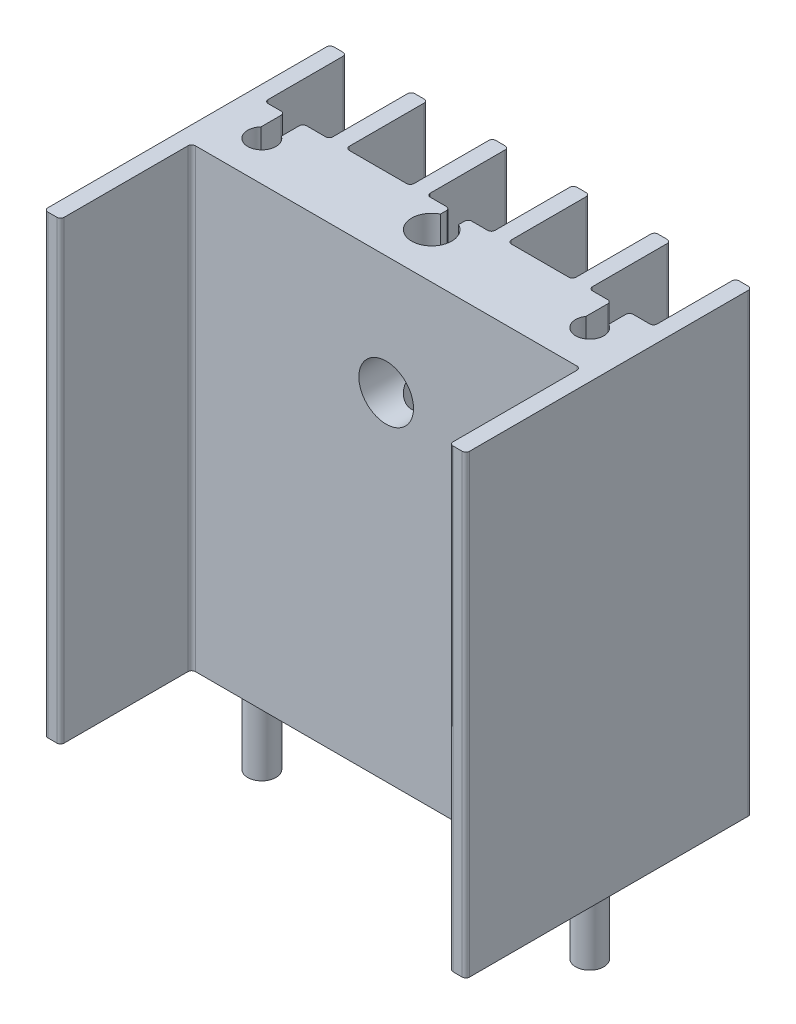
SolidWorks part; units mm, degrees
ref_plane "前视基准面" through (0, 0, 0) normal (0, 0, 1) x (1, 0, 0)
ref_plane "上视基准面" through (0, 0, 0) normal (0, 1, 0) x (1, 0, 0)
ref_plane "右视基准面" through (0, 0, 0) normal (1, 0, 0) x (0, 0, -1)
sketch "草图1" plane through (0, 0, 0) normal (0, 1, 0) x (1, 0, 0)
  line L0 (-11.375, -7.85) -> (-10.875, -7.85)
  line L1 (-11.575, -7.85) -> (11.575, -7.85) construction
  line L2 (-11.575, -7.65) -> (-11.575, 7.65)
  line L3 (-11.575, 7.85) -> (11.575, 7.85) construction
  line L4 (11.575, -7.65) -> (11.575, 7.65)
  line L5 (-11.575, -7.85) -> (11.575, 7.85) construction
  line L6 (-11.575, 7.85) -> (11.575, -7.85) construction
  line L7 (-10.675, -7.65) -> (-10.675, -0.65)
  line L8 (11.375, -7.85) -> (10.875, -7.85)
  line L9 (10.675, -7.65) -> (10.675, -0.65)
  line L10 (10.675, -0.65) -> (-10.675, -0.65)
  line L11 (-11.375, 7.85) -> (-10.875, 7.85)
  line L12 (-10.675, 7.65) -> (-10.675, 3.55)
  line L13 (-10.475, 3.35) -> (-9.7702, 3.35)
  line L14 (11.375, 7.85) -> (10.875, 7.85)
  line L15 (10.675, 7.65) -> (10.675, 3.55)
  line L16 (10.475, 3.35) -> (9.5581, 3.35)
  line L17 (7.125, 3.55) -> (7.125, 7.65)
  line L18 (6.925, 7.85) -> (6.425, 7.85)
  line L19 (-7.125, 3.55) -> (-7.125, 7.65)
  line L20 (-6.925, 7.85) -> (-6.425, 7.85)
  line L21 (-7.125, 3.35) -> (7.125, 3.35) construction
  line L22 (-6.225, 7.65) -> (-6.225, 3.55)
  line L23 (6.225, 7.65) -> (6.225, 3.55)
  line L24 (6.025, 3.35) -> (2.875, 3.35)
  line L25 (-6.025, 3.35) -> (-2.875, 3.35)
  line L26 (-2.675, 3.55) -> (-2.675, 7.65)
  line L27 (-2.475, 7.85) -> (-1.975, 7.85)
  line L28 (2.675, 3.55) -> (2.675, 7.65)
  line L29 (2.475, 7.85) -> (1.975, 7.85)
  line L30 (-1.775, 7.65) -> (-1.775, 3.55)
  line L31 (-1.575, 3.35) -> (-0.7, 3.35)
  line L32 (1.775, 3.55) -> (1.775, 7.65)
  line L33 (0, -0.65) -> (0, 1.85) construction
  line L34 (0, 7.85) -> (0, -7.85) construction
  line L36 (-0.5, 3.15) -> (-0.5, 2.8298)
  line L37 (0.5, 3.15) -> (0.5, 2.8298)
  line L38 (0.7, 3.35) -> (1.575, 3.35)
  line L40 (-9.5702, 3.15) -> (-9.5702, 2.0499)
  line L41 (-8.5702, 3.15) -> (-8.5702, 2.1699)
  line L42 (-8.3702, 3.35) -> (-7.325, 3.35)
  line L43 (8.1581, 3.35) -> (7.325, 3.35)
  line L44 (8.3581, 3.15) -> (8.3581, 1.9593)
  line L45 (9.3581, 3.15) -> (9.3581, 2.2123)
  arc A0 (-0.5, 2.8298) -> (0.5, 2.8298) centre (0, 1.85) ccw
  arc A1 (8.3581, 1.9593) -> (9.3581, 2.2123) centre (9, 1.525) ccw
  arc A2 (-8.5702, 2.1699) -> (-9.5702, 2.0499) centre (-9, 1.525) cw
  arc A3 (-10.675, 3.55) -> (-10.475, 3.35) centre (-10.475, 3.55) ccw
  arc A4 (-7.325, 3.35) -> (-7.125, 3.55) centre (-7.325, 3.55) ccw
  arc A5 (-6.225, 3.55) -> (-6.025, 3.35) centre (-6.025, 3.55) ccw
  arc A6 (-2.875, 3.35) -> (-2.675, 3.55) centre (-2.875, 3.55) ccw
  arc A7 (-1.775, 3.55) -> (-1.575, 3.35) centre (-1.575, 3.55) ccw
  arc A8 (1.575, 3.35) -> (1.775, 3.55) centre (1.575, 3.55) ccw
  arc A9 (2.875, 3.35) -> (2.675, 3.55) centre (2.875, 3.55) cw
  arc A10 (6.225, 3.55) -> (6.025, 3.35) centre (6.025, 3.55) cw
  arc A11 (7.325, 3.35) -> (7.125, 3.55) centre (7.325, 3.55) cw
  arc A12 (10.675, 3.55) -> (10.475, 3.35) centre (10.475, 3.55) cw
  arc A13 (9.3581, 3.15) -> (9.5581, 3.35) centre (9.5581, 3.15) cw
  arc A14 (8.3581, 3.15) -> (8.1581, 3.35) centre (8.1581, 3.15) ccw
  arc A15 (-9.7702, 3.35) -> (-9.5702, 3.15) centre (-9.7702, 3.15) cw
  arc A16 (-8.3702, 3.35) -> (-8.5702, 3.15) centre (-8.3702, 3.15) ccw
  arc A17 (-0.7, 3.35) -> (-0.5, 3.15) centre (-0.7, 3.15) cw
  arc A18 (0.7, 3.35) -> (0.5, 3.15) centre (0.7, 3.15) ccw
  arc A19 (-11.375, -7.85) -> (-11.575, -7.65) centre (-11.375, -7.65) cw
  arc A20 (-10.875, -7.85) -> (-10.675, -7.65) centre (-10.875, -7.65) ccw
  arc A21 (10.875, -7.85) -> (10.675, -7.65) centre (10.875, -7.65) cw
  arc A22 (11.375, -7.85) -> (11.575, -7.65) centre (11.375, -7.65) ccw
  arc A23 (11.375, 7.85) -> (11.575, 7.65) centre (11.375, 7.65) cw
  arc A24 (10.875, 7.85) -> (10.675, 7.65) centre (10.875, 7.65) ccw
  arc A25 (7.125, 7.65) -> (6.925, 7.85) centre (6.925, 7.65) ccw
  arc A26 (6.425, 7.85) -> (6.225, 7.65) centre (6.425, 7.65) ccw
  arc A27 (2.675, 7.65) -> (2.475, 7.85) centre (2.475, 7.65) ccw
  arc A28 (1.975, 7.85) -> (1.775, 7.65) centre (1.975, 7.65) ccw
  arc A29 (-1.975, 7.85) -> (-1.775, 7.65) centre (-1.975, 7.65) cw
  arc A30 (-2.675, 7.65) -> (-2.475, 7.85) centre (-2.475, 7.65) cw
  arc A31 (-6.425, 7.85) -> (-6.225, 7.65) centre (-6.425, 7.65) cw
  arc A32 (-7.125, 7.65) -> (-6.925, 7.85) centre (-6.925, 7.65) cw
  arc A33 (-10.875, 7.85) -> (-10.675, 7.65) centre (-10.875, 7.65) cw
  arc A34 (-11.575, 7.65) -> (-11.375, 7.85) centre (-11.375, 7.65) cw
  point P0 (0, 0)
  point P33 (9, 1.525)
  point P43 (0, 3.35)
  point P47 (-9.0702, 3.35)
  point P51 (8.8581, 3.35)
  point P54 (-10.675, 3.35)
  point P60 (-6.225, 3.35)
  point P63 (-2.675, 3.35)
  point P66 (-1.775, 3.35)
  point P69 (1.775, 3.35)
  point P72 (2.675, 3.35)
  point P75 (6.225, 3.35)
  point P81 (10.675, 3.35)
  point P84 (9.3581, 3.35)
  point P87 (8.3581, 3.35)
  point P90 (-9.5702, 3.35)
  point P93 (-8.5702, 3.35)
  point P96 (-0.5, 3.35)
  point P99 (0.5, 3.35)
  point P105 (-10.675, -7.85)
  point P108 (10.675, -7.85)
  point P117 (10.675, 7.85)
  point P120 (7.125, 7.85)
  point P123 (6.225, 7.85)
  point P126 (2.675, 7.85)
  point P129 (1.775, 7.85)
  point P132 (-1.775, 7.85)
  point P135 (-2.675, 7.85)
  point P138 (-6.225, 7.85)
  point P141 (-7.125, 7.85)
  point P144 (-10.675, 7.85)
  dimension "D16" = 2.575
  dimension "D18" = 1.55
  dimension "D22" = 0.2
  dimension "D1" = 23.15
  dimension "D2" = 15.7
  dimension "D3" = 0.9
  dimension "D4" = 7.2
  dimension "D5" = 0.9
  dimension "D6" = 4
  dimension "D7" = 3.55
  dimension "D8" = 3.55
  dimension "D9" = 0.9
  dimension "D10" = 0.9
  dimension "D11" = 3.55
  dimension "D12" = 3.55
  dimension "D13" = 0.9
  dimension "D14" = 0.9
  dimension "D15" = 2.5
  dimension "D17" = 2.175
  dimension "D19" = 1
  dimension "D20" = 1
  dimension "D21" = 1
extrude "凸台-拉伸1" add sketch "草图1" along normal blind 25 contours L20 A31 L22 A5 L25 A6 L26 A30 L27 A29 L30 A7 L31 A17 L36 A0 L37 A18 L38 A8 L32 A28 L29 A27 L28 A9 L24 A10 L23 A26 L18 A25 L17 A11 L43 A14 L44 A1 L45 A13 L16 A12 L15 A24 L14 A23 L4 A22 L8 A21 L9 L10 L7 A20 L0 A19 L2 A34 L11 A33 L12 A3 L13 A15 L40 A2 L41 A16 L42 A4 L19 A32
sketch "草图2" plane through (0, 0, 0) normal (0, -1, 0) x (1, 0, 0)
  circle A0 centre (-9, -1.525) radius 0.775
  circle A1 centre (9, -1.525) radius 0.775
extrude "凸台-拉伸2" add sketch "草图2" along normal blind 5 and the other way blind 20
fillet "圆角1" radius 0.2 2 edges at (10.675, 12.5, 0.65) (-10.675, 12.5, 0.65)
sketch "草图3" plane through (0, 0, 0.65) normal (0, 0, 1) x (1, 0, 0)
  line L0 (0, 0) -> (0, 25) construction
  line L1 (10.475, 25) -> (-10.475, 25) construction
  circle A0 centre (0, 18.5) radius 1.5
  dimension "D1" = 3
  dimension "D2" = 18.5
extrude "切除-拉伸1" cut sketch "草图3" against normal blind 10
